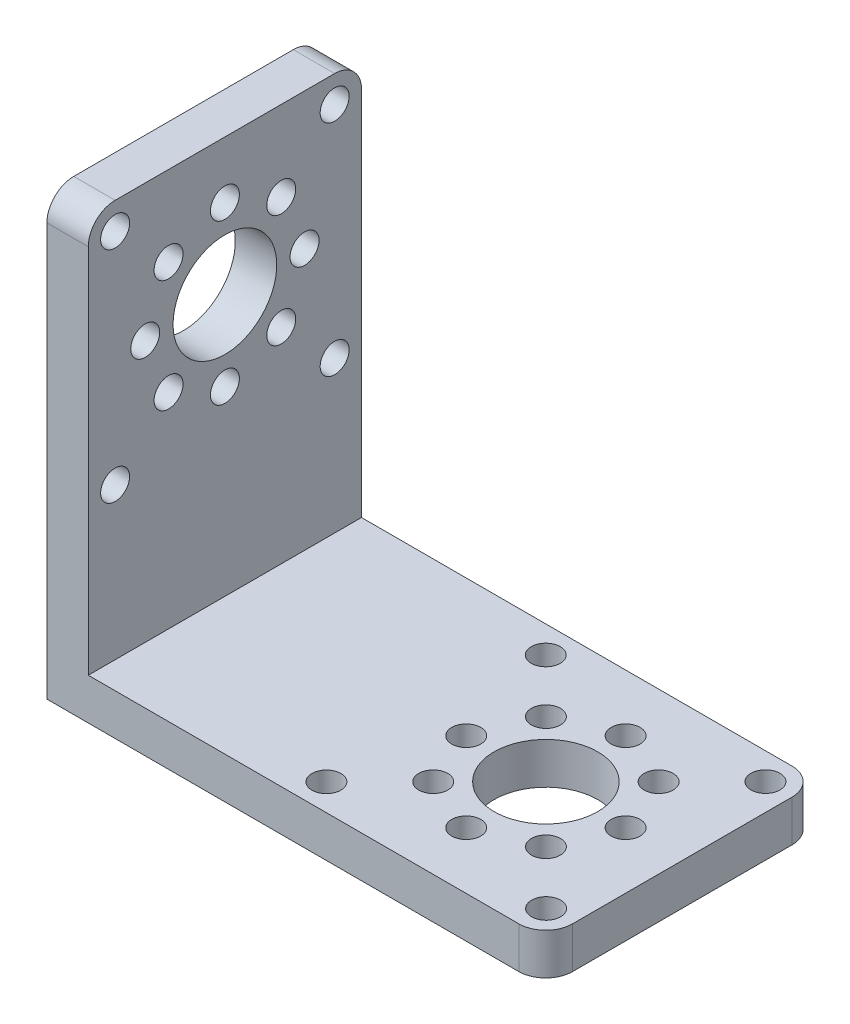
SolidWorks part; units mm, degrees
ref_plane "Front Plane" through (0, 0, 0) normal (0, 0, 1) x (1, 0, 0)
ref_plane "Top Plane" through (0, 0, 0) normal (0, 1, 0) x (1, 0, 0)
ref_plane "Right Plane" through (0, 0, 0) normal (1, 0, 0) x (0, 0, -1)
ref_plane "Plane1" through (0, 0, -16.764) normal (0, 0, -1) x (-1, 0, 0)
sketch "Sketch1" plane through (0, 0, -16.764) normal (0, 0, -1) x (-1, 0, 0)
  line L0 (33.147, 53.9115) -> (-28.067, 53.9115)
  line L1 (-28.067, 53.9115) -> (-28.067, 0)
  line L2 (-28.067, 0) -> (33.147, 0)
  line L3 (33.147, 0) -> (33.147, 53.9115)
extrude "Boss-Extrude1" add sketch "Sketch1" against normal blind 33.528
sketch "Sketch2" plane through (0, 0, 16.764) normal (0, 0, 1) x (1, 0, 0)
  line L0 (28.067, 53.9115) -> (-28.067, 53.9115)
  line L1 (-28.067, 53.9115) -> (-28.067, 5.08)
  line L2 (-28.067, 5.08) -> (28.067, 5.08)
  line L3 (28.067, 5.08) -> (28.067, 53.9115)
extrude "Cut-Extrude1" cut sketch "Sketch2" against normal through all
hole_wizard "Hole1" positions "Sketch4" profile "Sketch3" legacy
sketch "Sketch4" plane through (0, 0, 0) normal (0, -1, 0) x (-1, 0, 0)
  point P0 (-11.3309, 0)
sketch "Sketch3" plane through (11.3309, 0, 0) normal (1, 0, 0) x (0, 0, -1)
  line L0 (0, 0) -> (0, 53.9115)
  line L1 (0, 53.9115) -> (6.3627, 53.9115)
  line L2 (6.3627, 53.9115) -> (6.3627, 0)
  line L3 (6.3627, 0) -> (0, 0)
  line L4 (0, 110) -> (0, -10) construction
  dimension "Diameter" = 12.7254
  dimension "Depth" = 53.9115
hole_wizard "M3 Clearance Hole1" positions "Sketch6" profile "Sketch5" hole size "M3" standard "ANSI Metric"
sketch "Sketch6" plane through (0, 0, 0) normal (0, -1, 0) x (-1, 0, 0)
  point P0 (-4.4161, -6.9148)
  point P1 (-1.5519, 0)
  point P2 (-4.4161, 6.9148)
  point P3 (-11.3309, 9.779)
  point P4 (-18.2457, 6.9148)
  point P5 (-21.1099, 0)
  point P6 (-18.2457, -6.9148)
  point P7 (-11.3309, -9.779)
  point P8 (-24.7901, 13.4816)
  point P9 (2.1507, 13.4591)
  point P10 (2.1282, -13.4816)
  point P11 (-24.8126, -13.4591)
sketch "Sketch5" plane through (4.4161, 0, 6.9148) normal (1, 0, 0) x (0, 0, -1)
  line L0 (0, 0) -> (0, 53.9115)
  line L1 (0, 53.9115) -> (1.778, 53.9115)
  line L2 (1.778, 53.9115) -> (1.778, 0)
  line L5 (1.778, 0) -> (0, 0)
  line L11 (0, -6.35) -> (0, 107.95) construction
  dimension "Thru Hole Dia." = 3.556
  dimension "Thru Hole Depth" = 53.9115
hole_wizard "Hole2" positions "Sketch8" profile "Sketch7" legacy
sketch "Sketch8" plane through (-33.147, 0, 0) normal (-1, 0, 0) x (0, 0, 1)
  point P0 (0, 37.1475)
sketch "Sketch7" plane through (-33.147, 37.1475, 0) normal (0, 1, 0) x (0, 0, 1)
  line L0 (0, 0) -> (0, 61.214)
  line L1 (0, 61.214) -> (6.3627, 61.214)
  line L2 (6.3627, 61.214) -> (6.3627, 0)
  line L3 (6.3627, 0) -> (0, 0)
  line L4 (0, 110) -> (0, -10) construction
  dimension "Diameter" = 12.7254
  dimension "Depth" = 61.214
hole_wizard "M3 Clearance Hole2" positions "Sketch10" profile "Sketch9" hole size "M3" standard "ANSI Metric"
sketch "Sketch10" plane through (-33.147, 0, 0) normal (-1, 0, 0) x (0, 0, 1)
  point P0 (13.4704, 23.6771)
  point P1 (-13.4704, 23.6771)
  point P2 (-13.4704, 50.6179)
  point P3 (13.4704, 50.6179)
  point P4 (6.9148, 30.2327)
  point P5 (0, 27.3685)
  point P6 (-6.9148, 30.2327)
  point P7 (-9.779, 37.1475)
  point P8 (-6.9148, 44.0623)
  point P9 (0, 46.9265)
  point P10 (6.9148, 44.0623)
  point P11 (9.779, 37.1475)
sketch "Sketch9" plane through (-33.147, 23.6771, 13.4704) normal (0, 1, 0) x (0, 0, 1)
  line L0 (0, 0) -> (0, 61.214)
  line L1 (0, 61.214) -> (1.778, 61.214)
  line L2 (1.778, 61.214) -> (1.778, 0)
  line L5 (1.778, 0) -> (0, 0)
  line L11 (0, -6.35) -> (0, 107.95) construction
  dimension "Thru Hole Dia." = 3.556
  dimension "Thru Hole Depth" = 61.214
fillet "Fillet1" radius 3.2944 4 edges at (28.067, 2.54, 16.764) (28.067, 2.54, -16.764) (-30.607, 53.9115, 16.764) (-30.607, 53.9115, -16.764)
